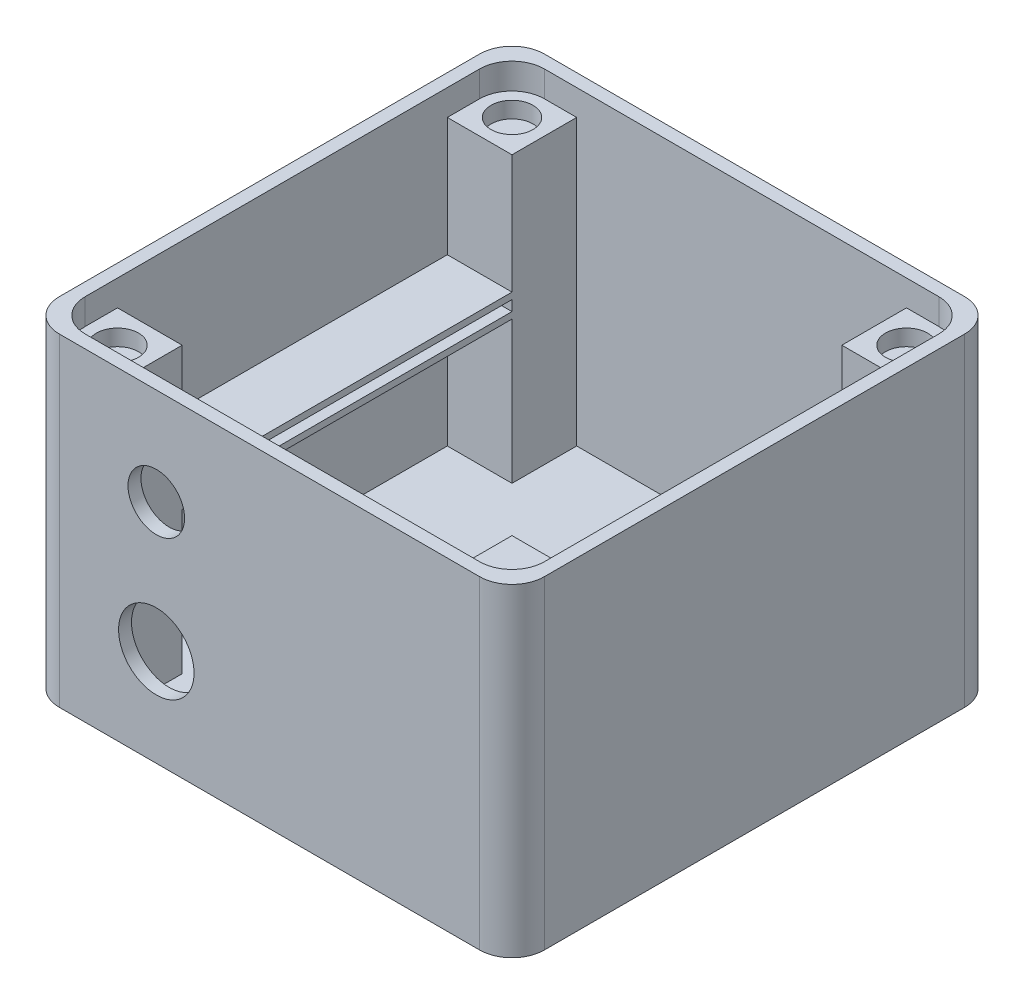
SolidWorks part; units mm, degrees
ref_plane "Front Plane" through (0, 0, 0) normal (0, 0, 1) x (1, 0, 0)
ref_plane "Top Plane" through (0, 0, 0) normal (0, 1, 0) x (1, 0, 0)
ref_plane "Right Plane" through (0, 0, 0) normal (1, 0, 0) x (0, 0, -1)
sketch "Sketch1" plane through (0, 0, 0) normal (0, 1, 0) x (1, 0, 0)
  line L1 (-37.5, 37.5) -> (37.5, 37.5)
  line L2 (-37.5, 37.5) -> (-37.5, -37.5)
  line L3 (-37.5, -37.5) -> (37.5, -37.5)
  line L4 (37.5, 37.5) -> (37.5, -37.5)
extrude "Boss-Extrude1" add sketch "Sketch1" along normal blind 50
sketch "Sketch2" plane through (0, 50, 0) normal (0, 1, 0) x (1, 0, 0)
  line L1 (-35.5, 35.5) -> (35.5, 35.5)
  line L2 (-35.5, 35.5) -> (-35.5, -35.5)
  line L3 (-35.5, -35.5) -> (35.5, -35.5)
  line L4 (35.5, 35.5) -> (35.5, -35.5)
extrude "Cut-Extrude1" cut sketch "Sketch2" against normal blind 48
sketch "Sketch3" plane through (0, 0, 0) normal (0, -1, 0) x (1, 0, 0)
  spline S0 degree 4 poles (8.3333, 0) (8.4517, 0.0028) (8.6878, 0.0244) (9.1569, 0.0918) (10.2805, 0.3456) (11.8943, 0.9272) (13.8988, 2.0138) (16.0129, 3.7308) (17.7608, 5.8215) (19.0497, 8.2251) (19.8147, 10.8899) (19.9856, 13.7023) (19.5393, 16.5283) (18.4949, 19.237) (16.9255, 21.6782) (14.8988, 23.7557) (12.4843, 25.3707) (9.8024, 26.4055) (6.9861, 26.795) (4.1098, 26.5372) (0.7228, 25.4877) (-2.9403, 23.3402) (-6.6474, 20.1127) (-10.371, 16.0536) (-13.9105, 11.8395) (-17.4966, 7.6627) (-20.9819, 4.1157) (-23.9874, 1.7583) (-26.3302, 0.5185) (-27.5545, 0.1252) (-28.0005, 0.0316) (-28.2549, 0.0035) (-28.2997, 0.0008) (-28.3221, 0) (-28.3333, 0) knots 0 0 0 0 0 0.005563 0.011126 0.022252 0.054052 0.085852 0.117652 0.149452 0.181251 0.213051 0.246908 0.280765 0.314622 0.348478 0.382335 0.416192 0.450048 0.482371 0.514693 0.55084 0.615485 0.680131 0.744776 0.809421 0.874066 0.938712 0.978092 0.987993 0.997893 0.998947 0.999473 1 1 1 1 1 construction
  spline S1 degree 4 poles (8.3333, 0) (8.4517, 0.0028) (8.6878, 0.0244) (9.1569, 0.0918) (10.2805, 0.3456) (11.8943, 0.9272) (13.8988, 2.0138) (16.0129, 3.7308) (17.7608, 5.8215) (19.0497, 8.2251) (19.8147, 10.8899) (19.9856, 13.7023) (19.5393, 16.5283) (18.4949, 19.237) (16.9255, 21.6782) (14.8988, 23.7557) (12.4843, 25.3707) (9.8024, 26.4055) (6.9861, 26.795) (4.1098, 26.5372) (0.7228, 25.4877) (-2.9403, 23.3402) (-6.6474, 20.1127) (-10.371, 16.0536) (-13.9105, 11.8395) (-17.4966, 7.6627) (-20.9819, 4.1157) (-23.9874, 1.7583) (-26.3302, 0.5185) (-27.5545, 0.1252) (-28.0005, 0.0316) (-28.2549, 0.0035) (-28.2997, 0.0008) (-28.3221, 0) (-28.3333, 0) knots 0 0 0 0 0 0.005563 0.011126 0.022252 0.054052 0.085852 0.117652 0.149452 0.181251 0.213051 0.246908 0.280765 0.314622 0.348478 0.382335 0.416192 0.450048 0.482371 0.514693 0.55084 0.615485 0.680131 0.744776 0.809421 0.874066 0.938712 0.978092 0.987993 0.997893 0.998947 0.999473 1 1 1 1 1
  spline S2 degree 4 poles (8.3333, 0) (8.4517, -0.0028) (8.6878, -0.0244) (9.1569, -0.0918) (10.2805, -0.3456) (11.8943, -0.9272) (13.8988, -2.0138) (16.0129, -3.7308) (17.7608, -5.8215) (19.0497, -8.2251) (19.8147, -10.8899) (19.9856, -13.7023) (19.5393, -16.5283) (18.4949, -19.237) (16.9255, -21.6782) (14.8988, -23.7557) (12.4843, -25.3707) (9.8024, -26.4055) (6.9861, -26.795) (4.1098, -26.5372) (0.7228, -25.4877) (-2.9403, -23.3402) (-6.6474, -20.1127) (-10.371, -16.0536) (-13.9105, -11.8395) (-17.4966, -7.6627) (-20.9819, -4.1157) (-23.9874, -1.7583) (-26.3302, -0.5185) (-27.5545, -0.1252) (-28.0005, -0.0316) (-28.2549, -0.0035) (-28.2997, -0.0008) (-28.3221, 0) (-28.3333, 0) knots 0 0 0 0 0 0.005563 0.011126 0.022252 0.054052 0.085852 0.117652 0.149452 0.181251 0.213051 0.246908 0.280765 0.314622 0.348478 0.382335 0.416192 0.450048 0.482371 0.514693 0.55084 0.615485 0.680131 0.744776 0.809421 0.874066 0.938712 0.978092 0.987993 0.997893 0.998947 0.999473 1 1 1 1 1 construction
  spline S3 degree 4 poles (8.3333, 0) (8.4517, -0.0028) (8.6878, -0.0244) (9.1569, -0.0918) (10.2805, -0.3456) (11.8943, -0.9272) (13.8988, -2.0138) (16.0129, -3.7308) (17.7608, -5.8215) (19.0497, -8.2251) (19.8147, -10.8899) (19.9856, -13.7023) (19.5393, -16.5283) (18.4949, -19.237) (16.9255, -21.6782) (14.8988, -23.7557) (12.4843, -25.3707) (9.8024, -26.4055) (6.9861, -26.795) (4.1098, -26.5372) (0.7228, -25.4877) (-2.9403, -23.3402) (-6.6474, -20.1127) (-10.371, -16.0536) (-13.9105, -11.8395) (-17.4966, -7.6627) (-20.9819, -4.1157) (-23.9874, -1.7583) (-26.3302, -0.5185) (-27.5545, -0.1252) (-28.0005, -0.0316) (-28.2549, -0.0035) (-28.2997, -0.0008) (-28.3221, 0) (-28.3333, 0) knots 0 0 0 0 0 0.005563 0.011126 0.022252 0.054052 0.085852 0.117652 0.149452 0.181251 0.213051 0.246908 0.280765 0.314622 0.348478 0.382335 0.416192 0.450048 0.482371 0.514693 0.55084 0.615485 0.680131 0.744776 0.809421 0.874066 0.938712 0.978092 0.987993 0.997893 0.998947 0.999473 1 1 1 1 1
extrude "Cut-Extrude6" cut sketch "Sketch3" against normal blind 2
fillet "Fillet4" radius 5 2 edges at (35.5, 26, 35.5) (37.5, 25, 37.5)
fillet "Fillet5" radius 5 2 edges at (-35.5, 26, 35.5) (-37.5, 25, 37.5)
fillet "Fillet6" radius 5 2 edges at (-37.5, 25, -37.5) (-35.5, 26, -35.5)
fillet "Fillet7" radius 5 2 edges at (35.5, 26, -35.5) (37.5, 25, -37.5)
sketch "Sketch4" plane through (0, 2, 0) normal (0, 1, 0) x (1, 0, 0)
  line L0 (35.5, -30.5) -> (35.5, 30.5) construction
  line L1 (25.5, 35.5) -> (35.5, 35.5)
  line L2 (25.5, 35.5) -> (25.5, 25.5)
  line L3 (25.5, 25.5) -> (35.5, 25.5)
  line L4 (35.5, 35.5) -> (35.5, 25.5)
  line L5 (30.5, 35.5) -> (-30.5, 35.5) construction
extrude "Boss-Extrude2" add sketch "Sketch4" along normal blind 44
sketch "Sketch5" plane through (0, 2, 0) normal (0, 1, 0) x (1, 0, 0)
  line L0 (-35.5, 30.5) -> (-35.5, -30.5) construction
  line L1 (-35.5, 25.5) -> (-25.5, 25.5)
  line L2 (-35.5, 25.5) -> (-35.5, 35.5)
  line L3 (-35.5, 35.5) -> (-25.5, 35.5)
  line L4 (-25.5, 25.5) -> (-25.5, 35.5)
  line L5 (25.5, 35.5) -> (-30.5, 35.5) construction
  line L6 (-30.5, -35.5) -> (30.5, -35.5) construction
  line L7 (-35.5, -25.5) -> (-25.5, -25.5)
  line L8 (-35.5, -25.5) -> (-35.5, -35.5)
  line L9 (-35.5, -35.5) -> (-25.5, -35.5)
  line L10 (-25.5, -25.5) -> (-25.5, -35.5)
  line L11 (25.5, -35.5) -> (35.5, -35.5)
  line L12 (25.5, -35.5) -> (25.5, -25.5)
  line L13 (25.5, -25.5) -> (35.5, -25.5)
  line L14 (35.5, -35.5) -> (35.5, -25.5)
  line L15 (35.5, -30.5) -> (35.5, 25.5) construction
extrude "Boss-Extrude3" add sketch "Sketch5" along normal blind 44
sketch "Sketch8" plane through (-35.5, 0, 0) normal (1, 0, 0) x (0, 0, -1)
  line L1 (-25.5, 25) -> (25.5, 25)
  line L2 (-25.5, 25) -> (-25.5, 24)
  line L3 (-25.5, 24) -> (25.5, 24)
  line L4 (25.5, 25) -> (25.5, 24)
extrude "Boss-Extrude4" add sketch "Sketch8" along normal blind 10
sketch "Sketch9" plane through (-35.5, 0, 0) normal (1, 0, 0) x (0, 0, -1)
  line L1 (25.5, 26.61) -> (-25.5, 26.61)
  line L2 (25.5, 26.61) -> (25.5, 27.61)
  line L3 (25.5, 27.61) -> (-25.5, 27.61)
  line L4 (-25.5, 26.61) -> (-25.5, 27.61)
extrude "Boss-Extrude5" add sketch "Sketch9" along normal blind 10
sketch "Sketch11" plane through (0, 46, 0) normal (0, 1, 0) x (1, 0, 0)
  circle A0 centre (30.5, 30.5) radius 3.25
  circle A2 centre (-30.5, 30.5) radius 3.25
  circle A3 centre (-30.5, -30.5) radius 3.25
extrude "Cut-Extrude8" cut sketch "Sketch11" against normal blind 2.5
sketch "Sketch12" plane through (0, 0, 35.5) normal (0, 0, -1) x (-1, 0, 0)
  circle A0 centre (17.5, 35) radius 4.375
extrude "Cut-Extrude9" cut sketch "Sketch12" against normal blind 2
sketch "Sketch13" plane through (0, 0, 35.5) normal (0, 0, -1) x (-1, 0, 0)
  circle A0 centre (17.5, 15) radius 5.838
extrude "Cut-Extrude10" cut sketch "Sketch13" against normal blind 2
